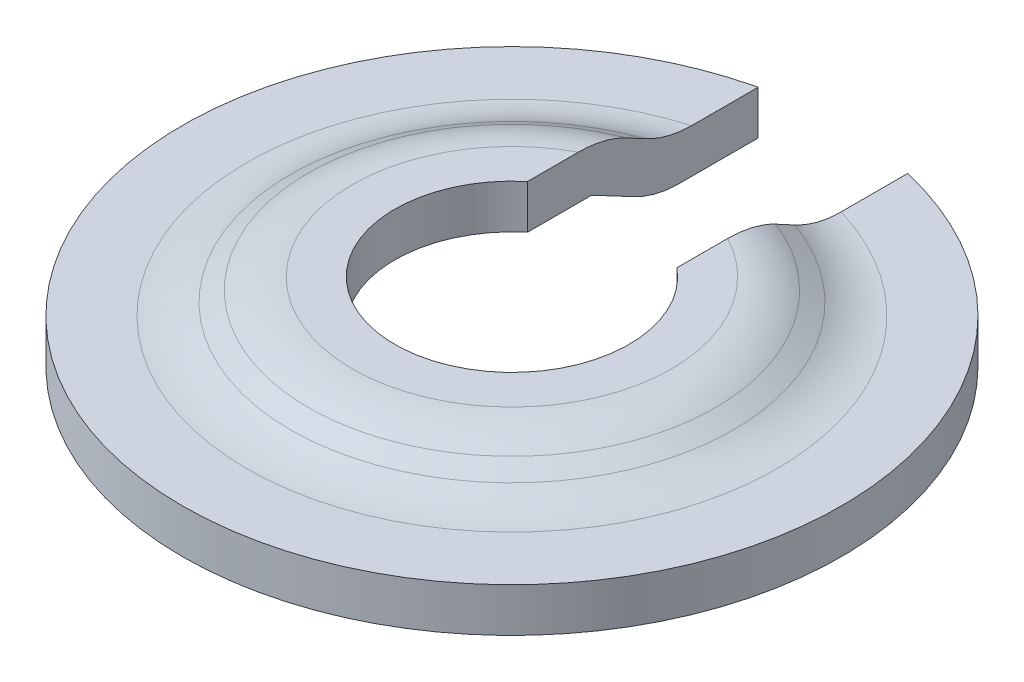
SolidWorks part; units mm, degrees
material "AISI 304"
ref_plane "Front Plane" through (0, 0, 0) normal (0, 0, 1) x (1, 0, 0)
ref_plane "Top Plane" through (0, 0, 0) normal (0, 1, 0) x (1, 0, 0)
ref_plane "Right Plane" through (0, 0, 0) normal (1, 0, 0) x (0, 0, -1)
sketch "Sketch2" plane through (0, 0, 0) normal (0, 0, 1) x (1, 0, 0)
  line L0 (0, 0) -> (0, 28.2919) construction
  line L1 (8, 2.3) -> (8, 5.3)
  line L2 (8, 5.3) -> (12.5, 5.3)
  line L3 (12.5, 5.3) -> (16.5, 3)
  line L4 (16.5, 3) -> (22.5, 3)
  line L5 (22.5, 3) -> (22.5, 0)
  line L6 (22.5, 0) -> (15.699, 0)
  line L7 (15.699, 0) -> (11.699, 2.3)
  line L8 (11.699, 2.3) -> (8, 2.3)
  dimension "D1" = 3
  dimension "D2" = 3
  dimension "D3" = 3
  dimension "D4" = 8
  dimension "D5" = 33
  dimension "D6" = 5.3
  dimension "D7" = 25
  dimension "D8" = 45
revolve "Revolve1" add sketch "Sketch2" angle 360 about L0
sketch "Sketch3" plane through (0, 0, 0) normal (0, 1, 0) x (1, 0, 0)
  line L0 (0, 0) -> (0, 23.3379) construction
  line L1 (-5.1, 21.9144) -> (-5.1, 6.1636)
  line L2 (5.1, 21.9144) -> (5.1, 6.1636)
  circle A0 centre (0, 0) radius 22.5 construction
  circle A1 centre (0, 0) radius 8 construction
  arc A2 (5.1, 21.9144) -> (-5.1, 21.9144) centre (0, 0) ccw
  arc A3 (5.1, 6.1636) -> (-5.1, 6.1636) centre (0, 0) ccw
  dimension "D1" = 10.2
extrude "Cut-Extrude1" cut sketch "Sketch3" along normal through all
fillet "Fillet1" radius 6 3 edges at (0, 0, 15.699) (0, 3, 16.5) (0, 5.3, 12.5)
